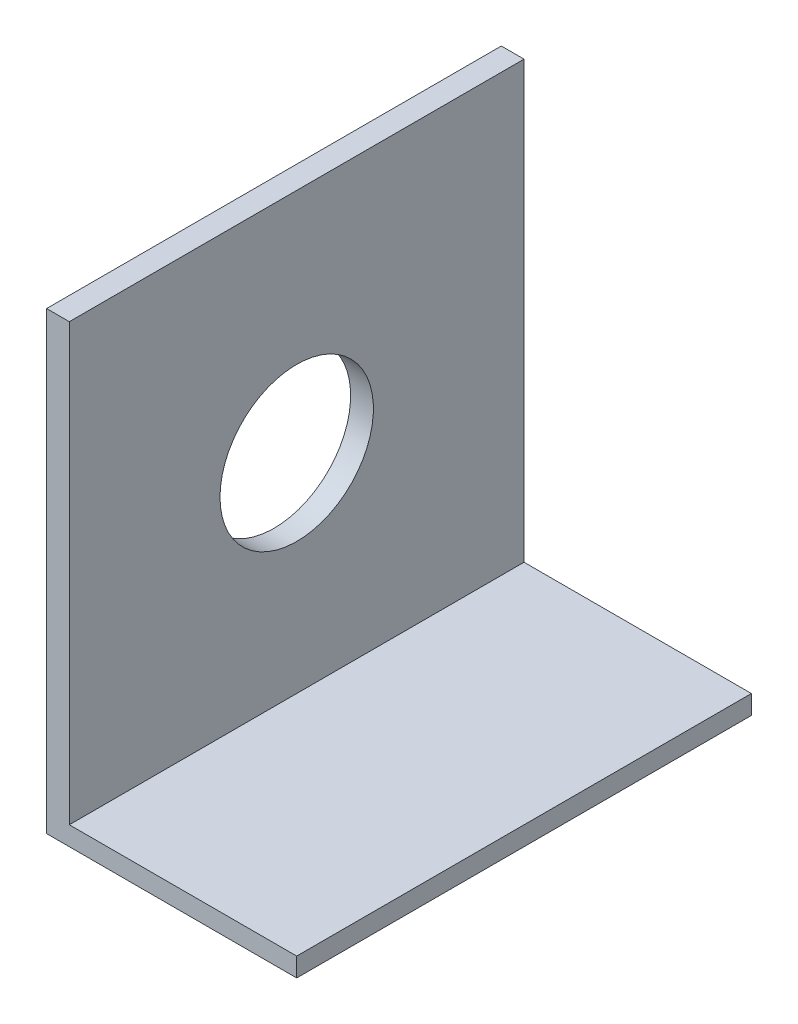
SolidWorks part; units mm, degrees
ref_plane "Front Plane" through (0, 0, 0) normal (0, 0, 1) x (1, 0, 0)
ref_plane "Top Plane" through (0, 0, 0) normal (0, 1, 0) x (1, 0, 0)
ref_plane "Right Plane" through (0, 0, 0) normal (1, 0, 0) x (0, 0, -1)
sketch "Sketch1" plane through (0, 0, 0) normal (0, 0, 1) x (1, 0, 0)
  line L0 (-28.6775, 27.108) -> (-28.6775, -12.892)
  line L1 (-28.6775, -12.892) -> (-6.6775, -12.892)
  line L2 (-6.6775, -12.892) -> (-6.6775, -11.2195)
  line L3 (-6.6775, -11.2195) -> (-26.6775, -11.2195)
  line L4 (-26.6775, -11.2195) -> (-26.6775, 27.108)
  line L5 (-26.6775, 27.108) -> (-27.7019, 27.108)
  line L6 (-27.7019, 27.108) -> (-28.6775, 27.108)
  dimension "D1" = 40
  dimension "D2" = 22
  dimension "D3" = 2
extrude "Boss-Extrude1" add sketch "Sketch1" along normal blind 40
sketch "Sketch2" plane through (-28.6775, 0, 0) normal (-1, 0, 0) x (0, 0, 1)
  line L0 (40, 27.108) -> (0, 27.108) construction
  circle A0 centre (20, 7.108) radius 6.7468
  point P4 (20, 27.108)
  point P7 (0, 0)
  dimension "D1" = 20
extrude "Cut-Extrude1" cut sketch "Sketch2" against normal blind 40
